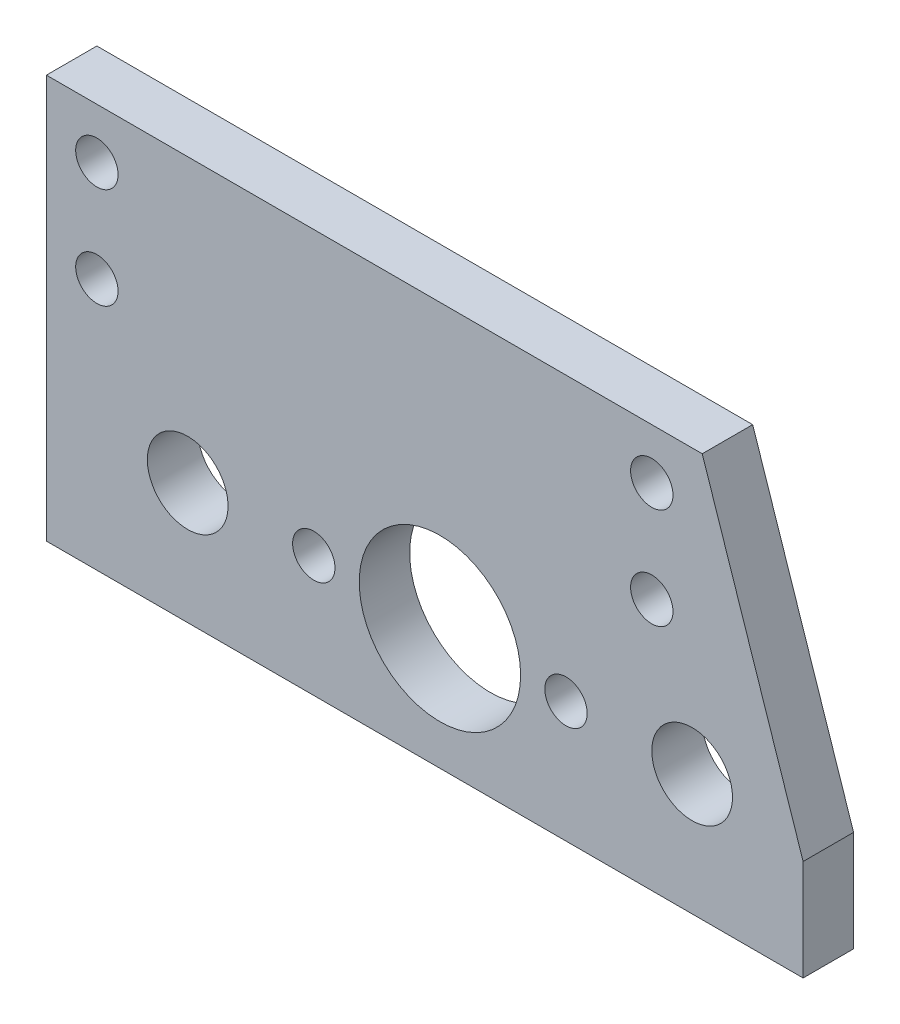
SolidWorks part; units mm, degrees
ref_plane "Front Plane" through (0, 0, 0) normal (0, 0, 1) x (1, 0, 0)
ref_plane "Top Plane" through (0, 0, 0) normal (0, 1, 0) x (1, 0, 0)
ref_plane "Right Plane" through (0, 0, 0) normal (1, 0, 0) x (0, 0, -1)
sketch "Sketch1" plane through (0, 0, 0) normal (0, 0, 1) x (1, 0, 0)
  line L3 (124.1115, 15.3385) -> (59.1115, 15.3385)
  line L4 (59.1115, 15.3385) -> (59.1115, -6.6615)
  line L8 (59.1115, -24.6615) -> (124.1115, -24.6615)
  line L9 (59.1115, -6.6615) -> (59.1115, -24.6615)
  line L10 (134.1115, -14.6615) -> (134.1115, -24.6615)
  line L11 (134.1115, -24.6615) -> (124.1115, -24.6615)
  line L12 (124.1115, 15.3385) -> (134.1115, -14.6615)
  line L13 (98.1115, -12.6615) -> (98.1115, 8.1586) construction
  circle A0 centre (64.1115, 10.3385) radius 2.1
  circle A1 centre (119.1115, 10.3385) radius 2.1
  circle A2 centre (64.1115, 0.3385) radius 2.1
  circle A3 centre (119.1115, 0.3385) radius 2.1
  circle A8 centre (123.1115, -12.6615) radius 4
  circle A9 centre (98.1115, -12.6615) radius 8
  circle A10 centre (85.6115, -12.6615) radius 2.1
  circle A11 centre (110.6115, -12.6615) radius 2.1
  circle A13 centre (73.1115, -12.6615) radius 4
  point P8 (0, 0)
  dimension "D7" = 4.2
  dimension "D8" = 4.2
  dimension "D9" = 4.2
  dimension "D10" = 4.2
  dimension "D11" = 5
  dimension "D12" = 5
  dimension "D13" = 10
  dimension "D14" = 5
  dimension "D15" = 1
  dimension "D16" = 10
  dimension "D17" = 10
  dimension "D18" = 5
  dimension "D19" = 8
  dimension "D20" = 16
  dimension "D21" = 25
  dimension "D23" = 4.2
  dimension "D24" = 12.5
  dimension "D25" = 4.2
  dimension "D26" = 12.5
  dimension "D2" = 65
  dimension "D3" = 30
  dimension "D4" = 40
  dimension "D5" = 22
extrude "Boss-Extrude1" add sketch "Sketch1" along normal blind 5
move or copy body "Body-Move/Copy1" [suppressed] bodies to move or copy 101
